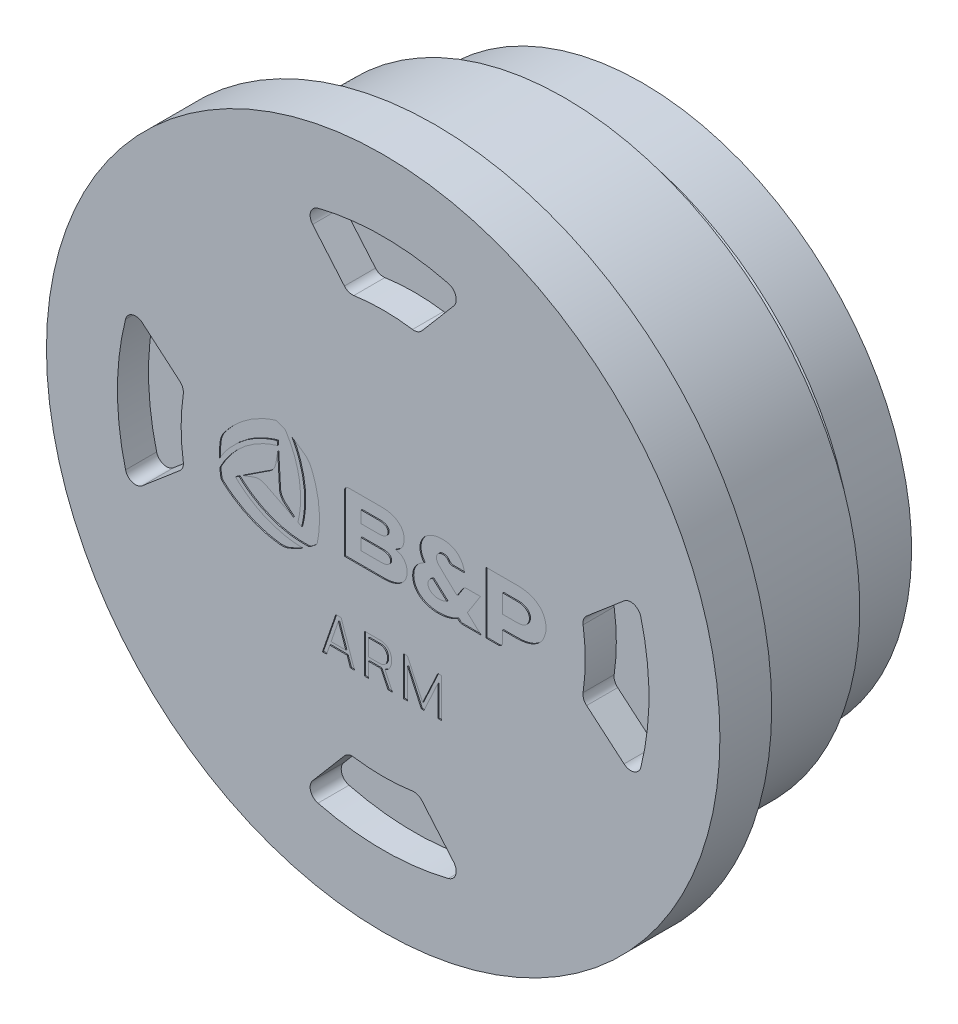
SolidWorks part; units mm, degrees
ref_plane "Alzado" through (0, 0, 0) normal (0, 0, 1) x (1, 0, 0)
ref_plane "Planta" through (0, 0, 0) normal (0, 1, 0) x (1, 0, 0)
ref_plane "Vista lateral" through (0, 0, 0) normal (1, 0, 0) x (0, 0, -1)
sketch "Croquis1" plane through (0, 0, 0) normal (1, 0, 0) x (0, 0, -1)
  line L0 (0, 20) -> (-20, 20)
  line L1 (0, 20) -> (0, 26)
  line L2 (0, 26) -> (-5.5, 26)
  line L3 (-20, 28.5) -> (-20, 32.5)
  line L4 (-20, 32.5) -> (-25, 32.5)
  line L5 (-25, 32.5) -> (-25, 0)
  line L6 (-20, 20) -> (-20, 0)
  line L7 (-20, 0) -> (-25, 0)
  line L8 (-7.5, 26) -> (-7.5, 28.5)
  line L9 (-7.5, 28.5) -> (-20, 28.5)
  arc A1 (-5.5, 26) -> (-7.5, 26) centre (-6.5, 27.118) cw
  dimension "D8" = 1.5
  dimension "D1" = 26
  dimension "D2" = 6
  dimension "D3" = 32.5
  dimension "D4" = 5
  dimension "D5" = 20
  dimension "D6" = 2.5
  dimension "D7" = 7.5
  dimension "D9" = 2
revolve "Revolución1" add sketch "Croquis1" angle 360 about L7
sketch "Croquis2" plane through (0, 0, 25) normal (0, 0, 1) x (1, 0, 0)
  line L0 (12.9941, 2.9603) -> (9.9298, 2.9603)
  line L1 (9.9298, 2.9603) -> (9.9298, -2.9483)
  line L2 (9.9298, -2.9483) -> (11.1069, -2.9483)
  line L3 (11.5319, -2.5232) -> (11.5319, -1.498)
  line L4 (11.5319, -1.498) -> (12.8614, -1.498)
  line L5 (12.9562, -0.1652) -> (11.5319, -0.1652)
  line L6 (11.5319, -0.1652) -> (11.5319, 1.6185)
  line L7 (11.5319, 1.6185) -> (12.9562, 1.6185)
  line L8 (8.1287, -1.7232) -> (8.1667, -1.6691)
  line L9 (8.1667, -1.6691) -> (9.3896, 0.2492)
  line L10 (9.3896, 0.2492) -> (8.047, 0.2492)
  line L11 (7.6902, 0.0552) -> (7.1333, -0.8045)
  line L12 (7.1333, -0.8045) -> (6.0715, 0.1772)
  line L13 (6.6766, 1.4563) -> (7.8514, 1.4563)
  line L14 (7.8514, 1.4563) -> (7.8481, 1.477)
  line L15 (7.1713, -2.6868) -> (7.3461, -2.8415)
  line L16 (7.6278, -2.9483) -> (9.4533, -2.9483)
  line L17 (9.4533, -2.9483) -> (8.1287, -1.7232)
  line L18 (4.7728, -0.5434) -> (6.1474, -1.7772)
  line L19 (-0.1945, 2.9603) -> (-3.3138, 2.9603)
  line L20 (-3.7388, 2.5353) -> (-3.7388, -2.9484)
  line L21 (-3.7388, -2.9484) -> (-0.0049, -2.9484)
  line L22 (-0.441, 0.5734) -> (-2.1367, 0.5734)
  line L23 (-2.1367, 0.5734) -> (-2.1367, 1.7175)
  line L24 (-2.1367, 1.7175) -> (-0.441, 1.7175)
  line L25 (-0.2135, -1.6875) -> (-2.1367, -1.6875)
  line L26 (-2.1367, -1.6875) -> (-2.1367, -0.5884)
  line L27 (-2.1367, -0.5884) -> (-0.185, -0.5884)
  line L28 (-7.8692, -2.5377) -> (-8.2315, -2.3551)
  line L29 (-10.2276, 3.4721) -> (-10.2047, 3.0671)
  line L30 (-14.2531, -1.5752) -> (-13.9134, -1.3526)
  line L31 (-12.471, -0.7001) -> (-13.5121, -1.0896)
  line L32 (-13.5121, -1.0896) -> (-10.9489, 0.5899)
  line L33 (-10.3608, 1.4912) -> (-10.1776, 2.5877)
  line L34 (-10.1776, 2.5877) -> (-10.0047, -0.4719)
  line L35 (-9.5182, -1.4319) -> (-8.6602, -2.1388)
  line L36 (-8.6602, -2.1388) -> (-11.3964, -0.7588)
  line L37 (0, 0) -> (0, -12) construction
  line L43 (-7.5, -12) -> (7.5, -12) construction
  line L44 (-5.8631, -12) -> (-4.568, -8.2394)
  line L45 (-4.568, -8.2394) -> (-4.0588, -8.2394)
  line L46 (-4.0588, -8.2394) -> (-2.7629, -12)
  line L47 (-2.7629, -12) -> (-3.1626, -12)
  line L48 (-3.1626, -12) -> (-3.4787, -11.0887)
  line L50 (-4.3169, -8.6725) -> (-5.0253, -10.7283)
  line L51 (-5.4634, -12) -> (-5.8631, -12)
  line L53 (-5.0253, -10.7283) -> (-3.6038, -10.7283)
  line L55 (-3.4787, -11.0887) -> (-5.1494, -11.0887)
  line L56 (-1.8104, -12) -> (-1.8104, -8.2394)
  line L57 (-1.8104, -8.2394) -> (-0.3589, -8.2394)
  line L59 (-0.2256, -10.5719) -> (-1.4266, -10.5719)
  line L60 (-1.4266, -10.5719) -> (-1.4266, -12)
  line L61 (-1.4266, -12) -> (-1.8104, -12)
  line L62 (0.4662, -12) -> (-0.2256, -10.5719)
  line L64 (0.1665, -10.4795) -> (0.9082, -12)
  line L65 (0.9082, -12) -> (0.4662, -12)
  line L66 (-1.4266, -10.2062) -> (-0.3687, -10.2062)
  line L67 (-0.3687, -8.6081) -> (-1.4266, -8.6081)
  line L68 (-1.4266, -8.6081) -> (-1.4266, -10.2062)
  line L69 (1.9809, -12) -> (1.9809, -8.2394)
  line L70 (1.9809, -8.2394) -> (2.333, -8.2394)
  line L71 (2.333, -8.2394) -> (3.8109, -11.4023)
  line L72 (3.8109, -11.4023) -> (5.2813, -8.2394)
  line L73 (5.2813, -8.2394) -> (5.6395, -8.2394)
  line L74 (5.6395, -8.2394) -> (5.6395, -11.9977)
  line L75 (5.6395, -11.9977) -> (5.2738, -11.9977)
  line L76 (5.2738, -11.9977) -> (5.2738, -9.0962)
  line L77 (5.2738, -9.0962) -> (3.9341, -12)
  line L78 (3.9341, -12) -> (3.6863, -12)
  line L79 (3.6863, -12) -> (2.3489, -9.0962)
  line L80 (2.3489, -9.0962) -> (2.3489, -12)
  line L81 (2.3489, -12) -> (1.9809, -12)
  line L82 (-5.1494, -11.0887) -> (-5.4634, -12)
  line L83 (-3.6038, -10.7283) -> (-4.3169, -8.6725)
  spline S0 degree 3 poles (15.3926, 1.9066) (15.1723, 2.2412) (14.8533, 2.5033) (14.4445, 2.6856) knots 1 1 1 1 2 2 2 2
  spline S1 degree 3 poles (14.4445, 2.6856) (14.0354, 2.8679) (13.5474, 2.9603) (12.9941, 2.9603) knots 2 2 2 2 3 3 3 3
  spline S2 degree 3 poles (11.1069, -2.9483) (11.3413, -2.9483) (11.5319, -2.7576) (11.5319, -2.5232) knots 6 6 6 6 7 7 7 7
  spline S3 degree 3 poles (12.8614, -1.498) (13.4401, -1.498) (13.952, -1.4025) (14.3829, -1.2143) knots 9 9 9 9 10 10 10 10
  spline S4 degree 3 poles (14.3829, -1.2143) (14.8137, -1.0261) (15.1486, -0.7549) (15.3783, -0.4083) knots 10 10 10 10 11 11 11 11
  spline S5 degree 3 poles (15.3783, -0.4083) (15.4905, -0.2388) (15.7227, 0.2723) (15.7238, 0.7712) knots 11 11 11 11 12 12 12 12
  spline S6 degree 3 poles (15.7238, 0.7712) (15.725, 1.2851) (15.4789, 1.7754) (15.3926, 1.9066) knots 12 12 12 12 13 13 13 13
  spline S7 degree 3 poles (14.0871, 0.5469) (14.04, 0.3732) (13.945, 0.2245) (13.8046, 0.105) knots 0 0 0 0 1 1 1 1
  spline S8 degree 3 poles (13.8046, 0.105) (13.5937, -0.0743) (13.3083, -0.1652) (12.9562, -0.1652) knots 1 1 1 1 2 2 2 2
  spline S9 degree 3 poles (12.9562, 1.6185) (13.3083, 1.6185) (13.5938, 1.5367) (13.8046, 1.3753) knots 5 5 5 5 6 6 6 6
  spline S10 degree 3 poles (13.8046, 1.3753) (13.94, 1.2715) (14.0333, 1.1421) (14.0818, 0.9905) knots 6 6 6 6 7 7 7 7
  spline S11 degree 3 poles (14.0818, 0.9905) (14.1263, 0.8518) (14.1281, 0.6984) (14.0871, 0.5469) knots 7 7 7 7 8 8 8 8
  spline S12 degree 3 poles (8.047, 0.2492) (7.9022, 0.2492) (7.7689, 0.1766) (7.6902, 0.0552) knots 3 3 3 3 4 4 4 4
  spline S13 degree 3 poles (6.0715, 0.1772) (5.713, 0.5057) (5.4658, 0.7496) (5.3369, 0.9021) knots 6 6 6 6 7 7 7 7
  spline S14 degree 3 poles (5.3369, 0.9021) (5.2079, 1.0544) (5.1426, 1.2165) (5.1426, 1.3839) knots 7 7 7 7 8 8 8 8
  spline S15 degree 3 poles (5.1426, 1.3839) (5.1426, 1.5573) (5.2015, 1.6981) (5.318, 1.8026) knots 8 8 8 8 9 9 9 9
  spline S16 degree 3 poles (5.318, 1.8026) (5.4344, 1.9072) (5.5827, 1.9603) (5.7587, 1.9603) knots 9 9 9 9 10 10 10 10
  spline S17 degree 3 poles (5.7587, 1.9603) (5.941, 1.9603) (6.0942, 1.8997) (6.2138, 1.7802) knots 10 10 10 10 11 11 11 11
  spline S18 degree 3 poles (6.2138, 1.7802) (6.2493, 1.7446) (6.2809, 1.7037) (6.3078, 1.6587) knots 11 11 11 11 12 12 12 12
  spline S19 degree 3 poles (6.3078, 1.6587) (6.3823, 1.5338) (6.5237, 1.4563) (6.6766, 1.4563) knots 12 12 12 12 13 13 13 13
  spline S20 degree 3 poles (7.8481, 1.477) (7.7693, 1.9758) (7.5607, 2.3824) (7.2281, 2.6853) knots 15 15 15 15 16 16 16 16
  spline S21 degree 3 poles (7.2281, 2.6853) (6.8507, 3.0289) (6.3404, 3.2031) (5.7114, 3.2031) knots 16 16 16 16 17 17 17 17
  spline S22 degree 3 poles (5.7114, 3.2031) (5.2837, 3.2031) (4.9026, 3.1228) (4.5785, 2.9645) knots 17 17 17 17 18 18 18 18
  spline S23 degree 3 poles (4.5785, 2.9645) (4.2546, 2.8061) (3.9994, 2.5894) (3.8201, 2.3205) knots 18 18 18 18 19 19 19 19
  spline S24 degree 3 poles (3.8201, 2.3205) (3.6408, 2.0516) (3.5499, 1.7486) (3.5499, 1.4199) knots 19 19 19 19 20 20 20 20
  spline S25 degree 3 poles (3.5499, 1.4199) (3.5499, 1.0612) (3.6807, 0.7006) (3.9385, 0.3482) knots 20 20 20 20 21 21 21 21
  spline S26 degree 3 poles (3.9385, 0.3482) (3.605, 0.1747) (3.3371, -0.0495) (3.1423, -0.3183) knots 21 21 21 21 22 22 22 22
  spline S27 degree 3 poles (3.1423, -0.3183) (2.9473, -0.5871) (2.8484, -0.9052) (2.8484, -1.2638) knots 22 22 22 22 23 23 23 23
  spline S28 degree 3 poles (2.8484, -1.2638) (2.8484, -1.6405) (2.9504, -1.9784) (3.1517, -2.268) knots 23 23 23 23 24 24 24 24
  spline S29 degree 3 poles (3.1517, -2.268) (3.353, -2.5579) (3.6432, -2.7866) (4.0144, -2.9479) knots 24 24 24 24 25 25 25 25
  spline S30 degree 3 poles (4.0144, -2.9479) (4.3855, -3.1093) (4.8193, -3.1911) (5.3037, -3.1911) knots 25 25 25 25 26 26 26 26
  spline S31 degree 3 poles (5.3037, -3.1911) (6.0272, -3.191) (6.6556, -3.0214) (7.1713, -2.6868) knots 26 26 26 26 27 27 27 27
  spline S32 degree 3 poles (7.3461, -2.8415) (7.4238, -2.9104) (7.5239, -2.9483) (7.6278, -2.9483) knots 29 29 29 29 30 30 30 30
  spline S33 degree 3 poles (6.1474, -1.7772) (5.8832, -1.9027) (5.6121, -1.9663) (5.3416, -1.9663) knots 0 0 0 0 1 1 1 1
  spline S34 degree 3 poles (5.3416, -1.9663) (5.0584, -1.9663) (4.8144, -1.892) (4.6164, -1.7456) knots 1 1 1 1 2 2 2 2
  spline S35 degree 3 poles (4.6164, -1.7456) (4.4183, -1.5993) (4.3178, -1.419) (4.3178, -1.2098) knots 2 2 2 2 3 3 3 3
  spline S36 degree 3 poles (4.3178, -1.2098) (4.3178, -1.0724) (4.3592, -0.9451) (4.441, -0.8316) knots 3 3 3 3 4 4 4 4
  spline S37 degree 3 poles (4.441, -0.8316) (4.5227, -0.7181) (4.6343, -0.6212) (4.7728, -0.5434) knots 4 4 4 4 5 5 5 5
  spline S38 degree 3 poles (2.2953, -1.0408) (2.265, -0.7992) (2.1745, -0.5779) (2.0264, -0.383) knots 0 0 0 0 1 1 1 1
  spline S39 degree 3 poles (2.0264, -0.383) (1.8469, -0.1469) (1.564, 0.0171) (1.2081, 0.0916) knots 1 1 1 1 2 2 2 2
  spline S40 degree 3 poles (1.2081, 0.0916) (1.8218, 0.3876) (1.9921, 0.7308) (2.0238, 1.3302) knots 2 2 2 2 3 3 3 3
  spline S41 degree 3 poles (2.0238, 1.3302) (2.0238, 1.8321) (1.8261, 2.2335) (1.436, 2.5235) knots 3 3 3 3 4 4 4 4
  spline S42 degree 3 poles (1.436, 2.5235) (1.0458, 2.8134) (0.4972, 2.9603) (-0.1945, 2.9603) knots 4 4 4 4 5 5 5 5
  spline S43 degree 3 poles (-3.3138, 2.9603) (-3.5482, 2.9603) (-3.7388, 2.7697) (-3.7388, 2.5353) knots 6 6 6 6 7 7 7 7
  spline S44 degree 3 poles (-0.0049, -2.9484) (0.7059, -2.9484) (1.2752, -2.7923) (1.6872, -2.4845) knots 9 9 9 9 10 10 10 10
  spline S45 degree 3 poles (1.6872, -2.4845) (2.0993, -2.1767) (2.3081, -1.7601) (2.3081, -1.2462) knots 10 10 10 10 11 11 11 11
  spline S46 degree 3 poles (2.3081, -1.2462) (2.3081, -1.1778) (2.3038, -1.1087) (2.2953, -1.0408) knots 11 11 11 11 12 12 12 12
  spline S47 degree 3 poles (0.4362, 0.9769) (0.3963, 0.8882) (0.3325, 0.8116) (0.2463, 0.749) knots 0 0 0 0 1 1 1 1
  spline S48 degree 3 poles (0.2463, 0.749) (0.0859, 0.6324) (-0.1453, 0.5734) (-0.441, 0.5734) knots 1 1 1 1 2 2 2 2
  spline S49 degree 3 poles (-0.441, 1.7175) (-0.133, 1.7175) (0.1014, 1.666) (0.2558, 1.5644) knots 5 5 5 5 6 6 6 6
  spline S50 degree 3 poles (0.2558, 1.5644) (0.3356, 1.5117) (0.3956, 1.4455) (0.434, 1.3677) knots 6 6 6 6 7 7 7 7
  spline S51 degree 3 poles (0.434, 1.3677) (0.4922, 1.2494) (0.493, 1.1034) (0.4362, 0.9769) knots 7 7 7 7 8 8 8 8
  spline S52 degree 3 poles (0.6878, -0.937) (0.7359, -1.0394) (0.7372, -1.1614) (0.6914, -1.2716) knots 0 0 0 0 1 1 1 1
  spline S53 degree 3 poles (0.6914, -1.2716) (0.6529, -1.3641) (0.5877, -1.445) (0.4975, -1.5119) knots 1 1 1 1 2 2 2 2
  spline S54 degree 3 poles (0.4975, -1.5119) (0.3403, -1.6284) (0.101, -1.6875) (-0.2135, -1.6875) knots 2 2 2 2 3 3 3 3
  spline S55 degree 3 poles (-0.185, -0.5884) (0.1104, -0.5884) (0.3401, -0.6369) (0.4975, -0.7325) knots 6 6 6 6 7 7 7 7
  spline S56 degree 3 poles (0.4975, -0.7325) (0.5852, -0.7859) (0.6492, -0.8546) (0.6878, -0.937) knots 7 7 7 7 8 8 8 8
  spline S57 degree 3 poles (-6.9849, 2.9301) (-7.1015, 3.1925) (-7.2819, 3.4216) (-7.5072, 3.5998) knots 0 0 0 0 1 1 1 1
  spline S58 degree 3 poles (-7.5072, 3.5998) (-7.908, 3.9166) (-8.3361, 4.2015) (-8.7881, 4.4501) knots 1 1 1 1 2 2 2 2
  spline S59 degree 3 poles (-8.7881, 4.4501) (-8.4953, 3.9294) (-8.2523, 3.3813) (-8.0613, 2.8093) knots 2 2 2 2 3 3 3 3
  spline S60 degree 3 poles (-8.0613, 2.8093) (-7.6591, 1.6048) (-7.5057, 0.3469) (-7.6053, -0.9297) knots 3 3 3 3 4 4 4 4
  spline S61 degree 3 poles (-7.6053, -0.9297) (-7.648, -1.4773) (-7.7364, -2.0141) (-7.8692, -2.5377) knots 4 4 4 4 5 5 5 5
  spline S62 degree 3 poles (-8.2315, -2.3551) (-8.1164, -1.8841) (-8.0375, -1.3978) (-7.9986, -0.899) knots 6 6 6 6 7 7 7 7
  spline S63 degree 3 poles (-7.9986, -0.899) (-7.84, 1.134) (-8.3664, 3.0653) (-9.3831, 4.6675) knots 7 7 7 7 8 8 8 8
  spline S64 degree 3 poles (-9.3831, 4.6675) (-9.4316, 4.7438) (-9.5019, 4.8039) (-9.585, 4.8397) knots 8 8 8 8 9 9 9 9
  spline S65 degree 3 poles (-9.585, 4.8397) (-9.7793, 4.9234) (-9.9772, 5.0006) (-10.1784, 5.0713) knots 9 9 9 9 10 10 10 10
  spline S66 degree 3 poles (-10.1784, 5.0713) (-10.2706, 5.1036) (-10.371, 5.1049) (-10.464, 5.0749) knots 10 10 10 10 11 11 11 11
  spline S67 degree 3 poles (-10.464, 5.0749) (-10.8599, 4.9471) (-11.2523, 4.7928) (-11.6387, 4.6111) knots 11 11 11 11 12 12 12 12
  spline S68 degree 3 poles (-11.6387, 4.6111) (-13.1903, 3.8816) (-14.4626, 2.7989) (-15.405, 1.504) knots 12 12 12 12 13 13 13 13
  spline S69 degree 3 poles (-15.405, 1.504) (-15.574, 1.2719) (-15.6822, 1.0011) (-15.7238, 0.717) knots 13 13 13 13 14 14 14 14
  spline S70 degree 3 poles (-15.7238, 0.717) (-15.7979, 0.2114) (-15.8305, -0.3019) (-15.8198, -0.8175) knots 14 14 14 14 15 15 15 15
  spline S71 degree 3 poles (-15.8198, -0.8175) (-15.5152, -0.3036) (-15.1621, 0.1808) (-14.7622, 0.6323) knots 15 15 15 15 16 16 16 16
  spline S72 degree 3 poles (-14.7622, 0.6323) (-13.9202, 1.5828) (-12.9075, 2.3447) (-11.7522, 2.8967) knots 16 16 16 16 17 17 17 17
  spline S73 degree 3 poles (-11.7522, 2.8967) (-11.2566, 3.1335) (-10.7475, 3.3254) (-10.2276, 3.4721) knots 17 17 17 17 18 18 18 18
  spline S74 degree 3 poles (-10.2047, 3.0671) (-10.6702, 2.9313) (-11.1307, 2.7564) (-11.5821, 2.5407) knots 19 19 19 19 20 20 20 20
  spline S75 degree 3 poles (-11.5821, 2.5407) (-13.422, 1.6616) (-14.8313, 0.24) (-15.7105, -1.4415) knots 20 20 20 20 21 21 21 21
  spline S76 degree 3 poles (-15.7105, -1.4415) (-15.7524, -1.5217) (-15.7693, -1.6126) (-15.7587, -1.7025) knots 21 21 21 21 22 22 22 22
  spline S77 degree 3 poles (-15.7587, -1.7025) (-15.7341, -1.9126) (-15.7021, -2.1226) (-15.6626, -2.3322) knots 22 22 22 22 23 23 23 23
  spline S78 degree 3 poles (-15.6626, -2.3322) (-15.6446, -2.4282) (-15.5955, -2.5158) (-15.523, -2.5813) knots 23 23 23 23 24 24 24 24
  spline S79 degree 3 poles (-15.523, -2.5813) (-15.2144, -2.8603) (-14.8846, -3.1229) (-14.5339, -3.3667) knots 24 24 24 24 25 25 25 25
  spline S80 degree 3 poles (-14.5339, -3.3667) (-13.1264, -4.3457) (-11.5526, -4.9062) (-9.96, -5.0749) knots 25 25 25 25 26 26 26 26
  spline S81 degree 3 poles (-9.96, -5.0749) (-9.6745, -5.1052) (-9.3859, -5.0635) (-9.119, -4.9574) knots 26 26 26 26 27 27 27 27
  spline S82 degree 3 poles (-9.119, -4.9574) (-8.6441, -4.7688) (-8.1833, -4.5405) (-7.7421, -4.2734) knots 27 27 27 27 28 28 28 28
  spline S83 degree 3 poles (-7.7421, -4.2734) (-8.3394, -4.2666) (-8.9356, -4.2029) (-9.5265, -4.0824) knots 28 28 28 28 29 29 29 29
  spline S84 degree 3 poles (-9.5265, -4.0824) (-10.7707, -3.8284) (-11.9368, -3.3324) (-12.9926, -2.6078) knots 29 29 29 29 30 30 30 30
  spline S85 degree 3 poles (-12.9926, -2.6078) (-13.4453, -2.2971) (-13.8661, -1.9521) (-14.2531, -1.5752) knots 30 30 30 30 31 31 31 31
  spline S86 degree 3 poles (-13.9134, -1.3526) (-13.5631, -1.6878) (-13.1817, -1.9995) (-12.7693, -2.2825) knots 32 32 32 32 33 33 33 33
  spline S87 degree 3 poles (-12.7693, -2.2825) (-11.088, -3.4364) (-9.1522, -3.9461) (-7.2563, -3.8668) knots 33 33 33 33 34 34 34 34
  spline S88 degree 3 poles (-7.2563, -3.8668) (-7.166, -3.8629) (-7.0788, -3.8321) (-7.0063, -3.778) knots 34 34 34 34 35 35 35 35
  spline S89 degree 3 poles (-7.0063, -3.778) (-6.8367, -3.6516) (-6.6709, -3.519) (-6.5092, -3.3801) knots 35 35 35 35 36 36 36 36
  spline S90 degree 3 poles (-6.5092, -3.3801) (-6.435, -3.3164) (-6.3836, -3.2301) (-6.363, -3.1344) knots 36 36 36 36 37 37 37 37
  spline S91 degree 3 poles (-6.363, -3.1344) (-6.2758, -2.7277) (-6.2132, -2.3106) (-6.1773, -1.8851) knots 37 37 37 37 38 38 38 38
  spline S92 degree 3 poles (-6.1773, -1.8851) (-6.0333, -0.1767) (-6.3347, 1.4665) (-6.9849, 2.9301) knots 38 38 38 38 39 39 39 39
  spline S93 degree 3 poles (-11.3964, -0.7588) (-11.7307, -0.5902) (-12.1203, -0.5689) (-12.471, -0.7001) knots 0 0 0 0 1 1 1 1
  spline S94 degree 3 poles (-10.9489, 0.5899) (-10.6357, 0.7951) (-10.4225, 1.1218) (-10.3608, 1.4912) knots 3 3 3 3 4 4 4 4
  spline S95 degree 3 poles (-10.0047, -0.4719) (-9.9836, -0.8458) (-9.8072, -1.1938) (-9.5182, -1.4319) knots 6 6 6 6 7 7 7 7
  spline S96 degree 3 poles (-0.3589, -8.2394) (-0.3175, -8.2386) (-0.2294, -8.2437) (-0.1414, -8.2514) (-0.0952, -8.2605) knots 0 0 0 0 0.468273 1 1 1 1
  spline S97 degree 3 poles (-0.0952, -8.2605) (-0.0021, -8.2748) (0.1337, -8.3089) (0.2978, -8.3897) (0.4063, -8.4636) (0.503, -8.5491) (0.5882, -8.6451) (0.6591, -8.7527) (0.7183, -8.8693) (0.764, -8.9942) (0.8096, -9.1725) (0.8208, -9.3124) (0.8213, -9.4068) knots 0 0 0 0 0.175501 0.258083 0.339067 0.419088 0.497787 0.577209 0.658114 0.74056 0.824221 1 1 1 1
  spline S98 degree 3 poles (0.8213, -9.4068) (0.8211, -9.4757) (0.8145, -9.5778) (0.7908, -9.7103) (0.767, -9.805) (0.735, -9.8958) (0.6962, -9.9831) (0.651, -10.0674) (0.598, -10.147) (0.5396, -10.2219) (0.4743, -10.2899) (0.402, -10.3494) (0.3245, -10.4027) (0.2459, -10.4466) (0.1918, -10.4698) (0.1665, -10.4795) knots 0 0 0 0 0.132777 0.196316 0.258884 0.320534 0.381536 0.442721 0.504317 0.565433 0.625446 0.685359 0.745346 0.806339 0.858432 0.858432 0.858432 0.858432
  spline S99 degree 3 poles (-0.3687, -10.2062) (-0.3322, -10.2054) (-0.2543, -10.2029) (-0.1772, -10.1908) (-0.1368, -10.1828) knots 0 0 0 0 0.46985 1 1 1 1
  spline S100 degree 3 poles (-0.1368, -10.1828) (-0.0759, -10.1698) (0.0115, -10.1404) (0.1148, -10.079) (0.1819, -10.0249) (0.2397, -9.9627) (0.29, -9.8949) (0.3325, -9.8219) (0.3671, -9.744) (0.3941, -9.6625) (0.4206, -9.5506) (0.4275, -9.4642) (0.4277, -9.4068) knots 0 0 0 0 0.179292 0.262884 0.344897 0.426486 0.506853 0.587465 0.669285 0.751857 0.834547 1 1 1 1
  spline S101 degree 3 poles (0.4277, -9.4068) (0.4275, -9.3494) (0.4207, -9.263) (0.394, -9.1509) (0.3671, -9.0688) (0.3325, -8.9901) (0.2901, -8.9165) (0.24, -8.8486) (0.1814, -8.7872) (0.1151, -8.7322) (0.0114, -8.6711) (-0.0759, -8.6415) (-0.1368, -8.6285) knots 0 0 0 0 0.165137 0.24767 0.330772 0.413098 0.494183 0.574397 0.655303 0.737617 0.821049 1 1 1 1
  spline S102 degree 3 poles (-0.1368, -8.6285) (-0.177, -8.6194) (-0.2544, -8.6107) (-0.3322, -8.6081) (-0.3687, -8.6081) knots 0 0 0 0 0.529955 1 1 1 1
  point P138 (0, -12)
  dimension "D1" = 12
  dimension "D2" = 15
extrude "Cortar-Extruir1" cut sketch "Croquis2" against normal blind 0.1 contours S91 S92 S57 S58 S59 S60 S61 L28 S62 S63 S64 S65 S66 S67 S68 S69 S70 S71 S72 S73 L29 S74 S75 S76 S77 S78 S79 S80 S81 S82 S83 S84 S85 L30 S86 S87 S88 S89 S90 L34 S95 L35 L36 S93 L31 L32 S94 L33 | S45 S46 S38 S39 S40 S41 S42 L19 S43 L20 L21 S44 S50 S51 S47 S48 L22 L23 L24 S49 S55 S56 S52 S53 S54 L25 L26 L27 | L15 S32 L16 L17 L8 L9 L10 S12 L11 L12 S13 S14 S15 S16 S17 S18 S19 L13 L14 S20 S21 S22 S23 S24 S25 S26 S27 S28 S29 S30 S31 S36 S37 L18 S33 S34 S35 | S5 S6 S0 S1 L0 L1 L2 S2 L3 L4 S3 S4 S10 S11 S7 S8 L5 L6 L7 S9 | S98 S97 S96 L57 L56 L61 L60 L59 L62 L65 L64 S102 S101 S100 S99 L66 L68 L67 | L81 L80 L79 L78 L77 L76 L75 L74 L73 L72 L71 L70 L69 | L55 L82 L51 L44 L45 L46 L47 L48 | L83 L50 L53
sketch "Croquis3" plane through (0, 0, 25) normal (0, 0, 1) x (1, 0, 0)
  line L1 (-6.9416, 24.1731) -> (-3.1793, 19.7457) construction
  line L3 (3.1793, 19.7457) -> (6.9416, 24.1731) construction
  line L6 (0, 0) -> (0, 25.15) construction
  line L7 (-7.8162, 24.4301) -> (-3.3764, 19.2055)
  line L8 (3.3764, 19.2055) -> (7.8162, 24.4301)
  arc A4 (3.1793, 19.7457) -> (-3.1793, 19.7457) centre (0, 0) ccw construction
  arc A5 (6.9416, 24.1731) -> (-6.9416, 24.1731) centre (0, 0) ccw construction
  arc A6 (3.3764, 19.2055) -> (-3.3764, 19.2055) centre (0, 0) ccw
  arc A7 (7.8162, 24.4301) -> (-7.8162, 24.4301) centre (0, 0) ccw
  point P12 (0, 0)
  point P14 (0, 0)
  point P15 (0, 0)
  point P16 (0, 0)
  dimension "D1" = 25.15
  dimension "D2" = 20
  dimension "D8" = 0.5
  dimension "D9" = 0.5
  dimension "D3" = 6.3586
  dimension "D4" = 13.8832
  dimension "D5" = 3.1793
  dimension "D6" = 0.5
  dimension "D7" = 0.5
  dimension "D10" = 24.4301
  dimension "D11" = 19.2055
extrude "Cortar-Extruir2" cut sketch "Croquis3" against normal blind 3
pattern_circular "MatrizC1" count 4 over 360 about axis through (0, 0, 0) along (0, 0, 1) of "Cortar-Extruir2"
fillet "Redondeo1" radius 1 16 edges at (-24.4301, -7.8162, 23.5) (-19.2055, -3.3764, 23.5) (-19.2055, 3.3764, 23.5) (-24.4301, 7.8162, 23.5) (7.8162, -24.4301, 23.5) (3.3764, -19.2055, 23.5) (-7.8162, -24.4301, 23.5) (-3.3764, -19.2055, 23.5) (19.2055, 3.3764, 23.5) (24.4301, 7.8162, 23.5) (19.2055, -3.3764, 23.5) (24.4301, -7.8162, 23.5) (3.3764, 19.2055, 23.5) (7.8162, 24.4301, 23.5) (-7.8162, 24.4301, 23.5) (-3.3764, 19.2055, 23.5)
